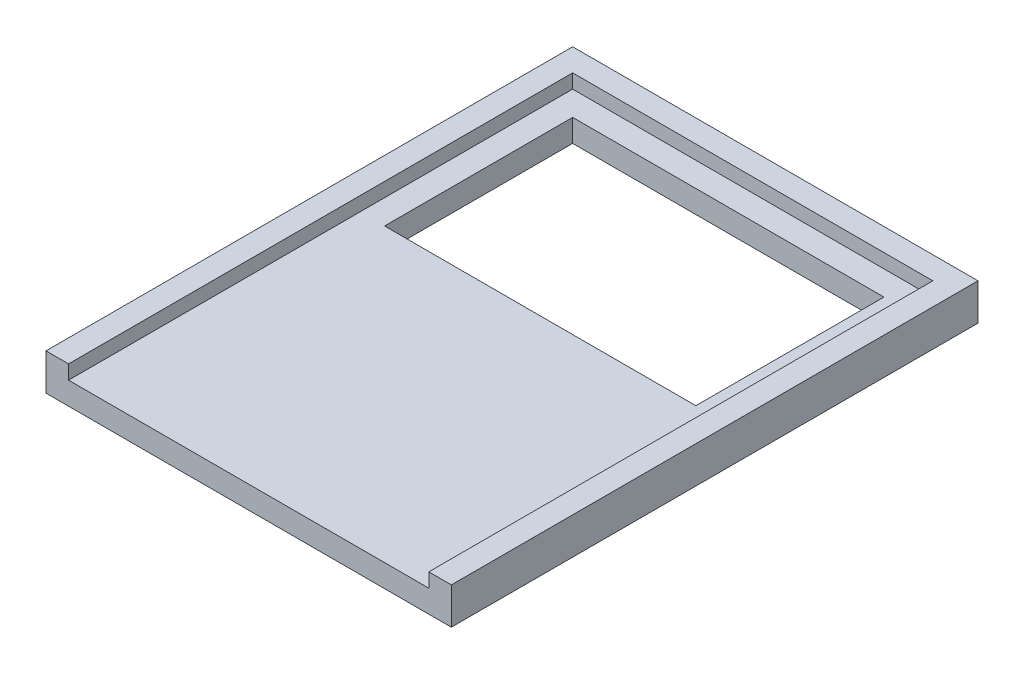
SolidWorks part; units mm, degrees
ref_plane "Plan de face" through (0, 0, 0) normal (0, 0, 1) x (1, 0, 0)
ref_plane "Plan de dessus" through (0, 0, 0) normal (0, 1, 0) x (1, 0, 0)
ref_plane "Plan de droite" through (0, 0, 0) normal (1, 0, 0) x (0, 0, -1)
sketch "Esquisse1" plane through (0, 0, 0) normal (0, 1, 0) x (1, 0, 0)
  line L1 (-215.5, 280) -> (215.5, 280)
  line L2 (-215.5, 280) -> (-215.5, -280)
  line L3 (-215.5, -280) -> (215.5, -280)
  line L4 (215.5, 280) -> (215.5, -280)
  line L5 (-165.5, 230) -> (165.5, 230)
  line L6 (-165.5, 230) -> (-165.5, 30)
  line L7 (-165.5, 30) -> (165.5, 30)
  line L8 (165.5, 230) -> (165.5, 30)
  point P4 (0, 280)
  point P6 (-215.5, 0)
  dimension "D1" = 431
  dimension "D2" = 560
  dimension "D3" = 50
  dimension "D4" = 50
  dimension "D5" = 200
  dimension "D6" = 50
extrude "Boss.-Extru.1" add sketch "Esquisse1" along normal blind 24
sketch "Esquisse2" plane through (0, 24, 0) normal (0, 1, 0) x (1, 0, 0)
  line L0 (-215.5, 280) -> (215.5, 280)
  line L1 (215.5, 280) -> (215.5, -280)
  line L2 (215.5, -280) -> (191.5, -280)
  line L3 (-215.5, -280) -> (215.5, -280) construction
  line L4 (191.5, -280) -> (191.5, 256)
  line L5 (191.5, 256) -> (-191.5, 256)
  line L6 (-191.5, 256) -> (-191.5, -280)
  line L7 (-191.5, -280) -> (-215.5, -280)
  line L8 (-215.5, -280) -> (-215.5, 280)
  dimension "D1" = 24
  dimension "D2" = 24
  dimension "D3" = 24
extrude "Boss.-Extru.2" add sketch "Esquisse2" along normal blind 15
